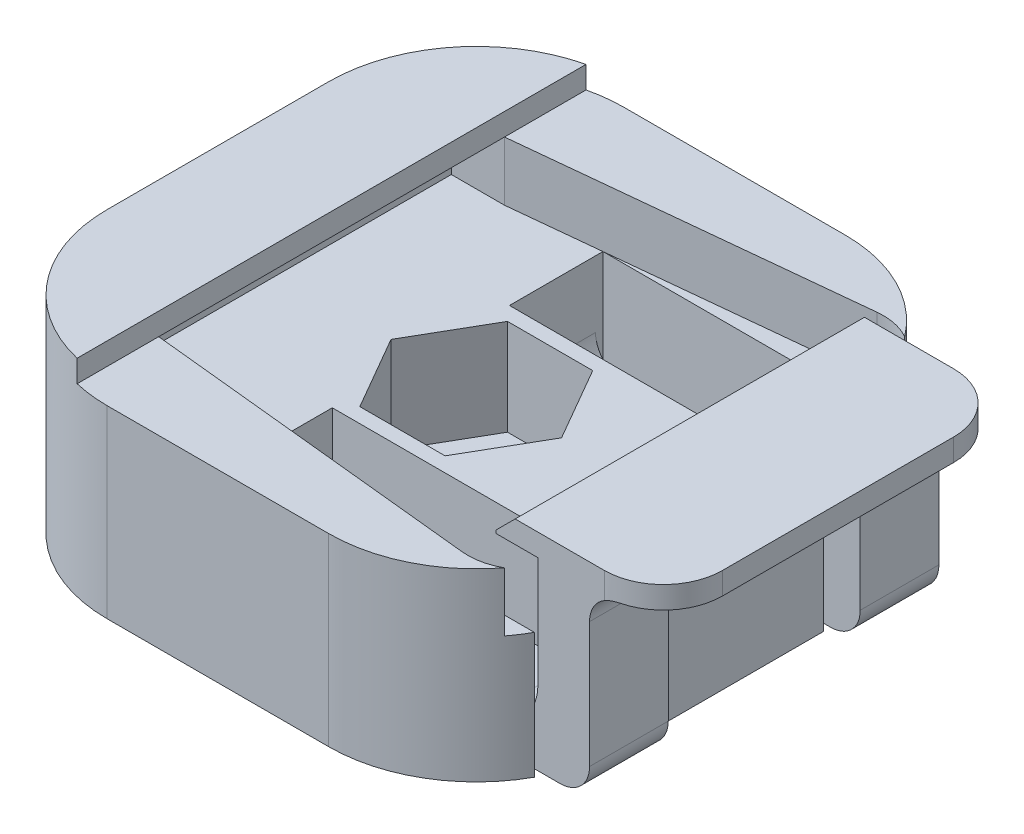
SolidWorks part; units mm, degrees
ref_plane "Plan de face" through (0, 0, 0) normal (0, 0, 1) x (1, 0, 0)
ref_plane "Plan de dessus" through (0, 0, 0) normal (0, 1, 0) x (1, 0, 0)
ref_plane "Plan de droite" through (0, 0, 0) normal (1, 0, 0) x (0, 0, -1)
sketch "Esquisse1" plane through (0, 0, 0) normal (0, 1, 0) x (1, 0, 0)
  line L1 (-17.5, 17.5) -> (17.5, 17.5)
  line L2 (-17.5, 17.5) -> (-17.5, -17.5)
  line L3 (-17.5, -17.5) -> (17.5, -17.5)
  line L4 (17.5, 17.5) -> (17.5, -17.5)
  line L5 (-17.5, 17.5) -> (17.5, -17.5) construction
  line L6 (-17.5, -17.5) -> (17.5, 17.5) construction
  point P0 (0, 0)
  dimension "D1" = 35
  dimension "D2" = 35
extrude "Boss.-Extru.1" add sketch "Esquisse1" along normal blind 14
fillet "Congé1" radius 10 4 edges at (-17.5, 7, -17.5) (17.5, 7, -17.5) (17.5, 7, 17.5) (-17.5, 7, 17.5)
sketch "Esquisse2" plane through (0, 14, 0) normal (0, 1, 0) x (1, 0, 0)
  circle A0 centre (0, 0) radius 3
  dimension "D1" = 6
extrude "Enlèv. mat.-Extru.1" cut sketch "Esquisse2" against normal through all
sketch "Esquisse3" plane through (0, 14, 0) normal (0, 1, 0) x (1, 0, 0)
  line L1 (5.7735, 0) -> (2.8868, 5)
  line L2 (2.8868, 5) -> (-2.8868, 5)
  line L3 (-2.8868, 5) -> (-5.7735, 0)
  line L4 (-5.7735, 0) -> (-2.8868, -5)
  line L5 (-2.8868, -5) -> (2.8868, -5)
  line L6 (2.8868, -5) -> (5.7735, 0)
  circle A0 centre (0, 0) radius 5 construction
  dimension "D1" = 10
extrude "Enlèv. mat.-Extru.2" cut sketch "Esquisse3" against normal blind 12
sketch "Esquisse4" plane through (0, 14, 0) normal (0, 1, 0) x (1, 0, 0)
  line L0 (-17.5, 7.5) -> (-17.5, -7.5) construction
  line L1 (-9.8, 19.5329) -> (21.5343, 19.5329)
  line L2 (-9.8, 19.5329) -> (-9.8, -19.6403)
  line L3 (-9.8, -19.6403) -> (21.5343, -19.6403)
  line L4 (21.5343, 19.5329) -> (21.5343, -19.6403)
  dimension "D1" = 7.7
extrude "Enlèv. mat.-Extru.3" cut sketch "Esquisse4" against normal blind 1.5
sketch "Esquisse5" plane through (0, 12.5, 0) normal (0, 1, 0) x (1, 0, 0)
  line L0 (-9.8, 11.71) -> (-9.8, -11.71)
  line L1 (-9.8, -11.71) -> (13.0933, -14.0496)
  line L2 (17.5, -10.0704) -> (17.5, 10.0704)
  line L3 (13.0933, 14.0496) -> (-9.8, 11.71)
  line L4 (-9.8, 17.2319) -> (-9.8, -17.2319) construction
  line L5 (17.5, -7.5) -> (17.5, 7.5) construction
  arc A0 (13.0933, -14.0496) -> (17.5, -10.0704) centre (13.5, -10.0704) ccw
  arc A1 (17.5, 10.0704) -> (13.0933, 14.0496) centre (13.5, 10.0704) ccw
  point P8 (-9.8, 0)
  point P10 (17.5, 0)
  point P13 (17.5, -14.5)
  point P16 (17.5, 14.5)
  dimension "D7" = 4
  dimension "D1" = 0
  dimension "D2" = 0
  dimension "D3" = 23.42
  dimension "D4" = 0
  dimension "D5" = 0
  dimension "D6" = 29
extrude "Enlèv. mat.-Extru.4" cut sketch "Esquisse5" against normal blind 4
sketch "Esquisse6" plane through (-9.8, 0, 0) normal (1, 0, 0) x (0, 0, -1)
  line L1 (-11.71, 8.5) -> (11.71, 8.5)
  line L2 (-11.71, 8.5) -> (-11.71, 12.5)
  line L3 (-11.71, 12.5) -> (11.71, 12.5)
  line L4 (11.71, 8.5) -> (11.71, 12.5)
extrude "Enlèv. mat.-Extru.5" cut sketch "Esquisse6" against normal blind 3.6
fillet "Congé2" radius 3 1 edges at (-13.4, 12.5, 0)
sketch "Esquisse7" plane through (0, 8.5, 0) normal (0, 1, 0) x (1, 0, 0)
  line L0 (-3.7528, -6) -> (16, -6)
  line L1 (-3.7528, -6) -> (-3.7528, -12.328)
  line L2 (-9.8, -11.71) -> (13.0933, -14.0496) construction
  line L3 (-3.7528, -12.328) -> (16, -12.328)
  line L4 (16, -12.328) -> (16, -6)
  line L5 (17.5, -7.5) -> (17.5, 7.5) construction
  line L6 (0, 0) -> (28.4672, 0) construction
  line L7 (-3.7528, 12.328) -> (16, 12.328)
  line L8 (-3.7528, 6) -> (-3.7528, 12.328)
  line L9 (-3.7528, 6) -> (16, 6)
  line L10 (16, 12.328) -> (16, 6)
  line L11 (2.8868, -5) -> (-2.8868, -5) construction
  dimension "D1" = 1.5
  dimension "D2" = 1
extrude "Enlèv. mat.-Extru.6" cut sketch "Esquisse7" against normal up to surface (6.5 mm away) up to face at (0, 2, 0)
sketch "Esquisse8" plane through (0, 2, 0) normal (0, 1, 0) x (1, 0, 0)
  line L1 (-3.7528, 6) -> (21.9493, 6)
  line L2 (-3.7528, 6) -> (-3.7528, 6.5)
  line L3 (-3.7528, 6.5) -> (21.9493, 6.5)
  line L4 (21.9493, 6) -> (21.9493, 6.5)
  line L5 (-3.7528, 12.328) -> (21.9493, 12.328)
  line L6 (-3.7528, 12.328) -> (-3.7528, 11.828)
  line L7 (-3.7528, 11.828) -> (21.9493, 11.828)
  line L8 (21.9493, 12.328) -> (21.9493, 11.828)
  line L9 (-3.7528, -6) -> (25.2587, -6)
  line L10 (-3.7528, -6) -> (-3.7528, -6.5)
  line L11 (-3.7528, -6.5) -> (25.2587, -6.5)
  line L12 (25.2587, -6) -> (25.2587, -6.5)
  line L13 (-3.7528, -12.328) -> (29.7665, -12.328)
  line L14 (-3.7528, -12.328) -> (-3.7528, -11.828)
  line L15 (-3.7528, -11.828) -> (29.7665, -11.828)
  line L16 (29.7665, -12.328) -> (29.7665, -11.828)
  dimension "D1" = 0.5
  dimension "D2" = 0.5
  dimension "D3" = 0.5
  dimension "D4" = 0.5
extrude "Enlèv. mat.-Extru.7" cut sketch "Esquisse8" against normal through all both and the other way through all
sketch "Esquisse9" plane through (0, 8.5, 0) normal (0, 1, 0) x (1, 0, 0)
  line L4 (17.5, -7.5) -> (17.5, -6.5)
  line L5 (17.5, -7.5) -> (17.5, -6.5)
  line L6 (16, -11.828) -> (16.5149, -11.828)
  line L7 (17.5, -6.5) -> (16, -6.5)
  line L8 (16, -6.5) -> (16, -11.828)
  line L9 (16, -11.828) -> (16.5149, -11.828)
  line L10 (17.5, -6.5) -> (16, -6.5)
  line L11 (16, -6.5) -> (16, -11.828)
  line L12 (17.5, 6.5) -> (17.5, 7.5)
  line L13 (17.5, 6.5) -> (17.5, 7.5)
  line L15 (16.5149, 11.828) -> (16, 11.828)
  line L16 (16, 11.828) -> (16, 6.5)
  line L17 (16, 6.5) -> (17.5, 6.5)
  line L18 (16.5149, 11.828) -> (16, 11.828)
  line L19 (16, 11.828) -> (16, 6.5)
  line L20 (16, 6.5) -> (17.5, 6.5)
  arc A2 (16.5149, -11.828) -> (17.5, -7.5) centre (7.5, -7.5) ccw
  arc A3 (16.5149, -11.828) -> (17.5, -7.5) centre (7.5, -7.5) ccw
  arc A5 (17.5, 7.5) -> (16.5149, 11.828) centre (7.5, 7.5) ccw
  arc A6 (17.5, 7.5) -> (16.5149, 11.828) centre (7.5, 7.5) ccw
  dimension "D1" = 0
  dimension "D2" = 0
extrude "Boss.-Extru.2" add sketch "Esquisse9" along normal up to surface (4 mm away) up to face at (1.5731, 12.5, 15.4553)
sketch "Esquisse10" plane through (0, 12.5, 0) normal (0, 1, 0) x (1, 0, 0)
  line L0 (-3.7528, 11.828) -> (16, 11.828) construction
  line L1 (13.16, 11.828) -> (20.5, 11.828)
  line L2 (13.16, 11.828) -> (13.16, -11.828)
  line L3 (13.16, -11.828) -> (20.5, -11.828)
  line L4 (24.5, 7.828) -> (24.5, -7.828)
  line L5 (17.5, -6) -> (17.5, 6) construction
  line L6 (16, -11.828) -> (16.5149, -11.828) construction
  arc A0 (20.5, -11.828) -> (24.5, -7.828) centre (20.5, -7.828) ccw
  arc A1 (20.5, 11.828) -> (24.5, 7.828) centre (20.5, 7.828) cw
  point P12 (24.5, 11.828)
  dimension "D3" = 4
  dimension "D1" = 11.34
  dimension "D2" = 7
extrude "Boss.-Extru.3" add sketch "Esquisse10" along normal up to surface (1.5 mm away) up to face at (-14.4961, 14, 0)
chamfer "Chanfrein1" distance 1.3 angle 45 1 edges at (13.16, 14, 0)
fillet "Congé3" radius 3 2 edges at (16, 2, 9.164) (16, 2, -9.164)
sketch "Esquisse11" plane through (17.5, 0, 0) normal (1, 0, 0) x (0, 0, -1)
  line L0 (7.5, 12.5) -> (11.828, 12.5) construction
  line L1 (-6.5, 12.5) -> (-11.828, 12.5)
  line L2 (-6.5, 12.5) -> (-6.5, 0)
  line L3 (-6.5, 0) -> (-11.828, 0)
  line L4 (-11.828, 12.5) -> (-11.828, 0)
  line L5 (6.5, 0) -> (11.828, 0)
  line L6 (6.5, 0) -> (6.5, 12.5)
  line L7 (6.5, 12.5) -> (11.828, 12.5)
  line L8 (11.828, 0) -> (11.828, 12.5)
  line L9 (11.828, 12.5) -> (11.828, 0) construction
  line L10 (-11.828, 12.5) -> (-7.5, 12.5) construction
  dimension "D1" = 0
  dimension "D2" = 0
  dimension "D3" = 0
extrude "Boss.-Extru.4" add sketch "Esquisse11" against normal up to body and the other way blind 2
fillet "Congé4" radius 2 4 edges at (19.5, 12.5, -9.164) (19.5, 12.5, 9.164) (19.5, 0, -9.164) (19.5, 0, 9.164)
fillet "Congé5" radius 2 2 edges at (-3.7528, 2, -9.164) (-3.7528, 2, 9.164)
